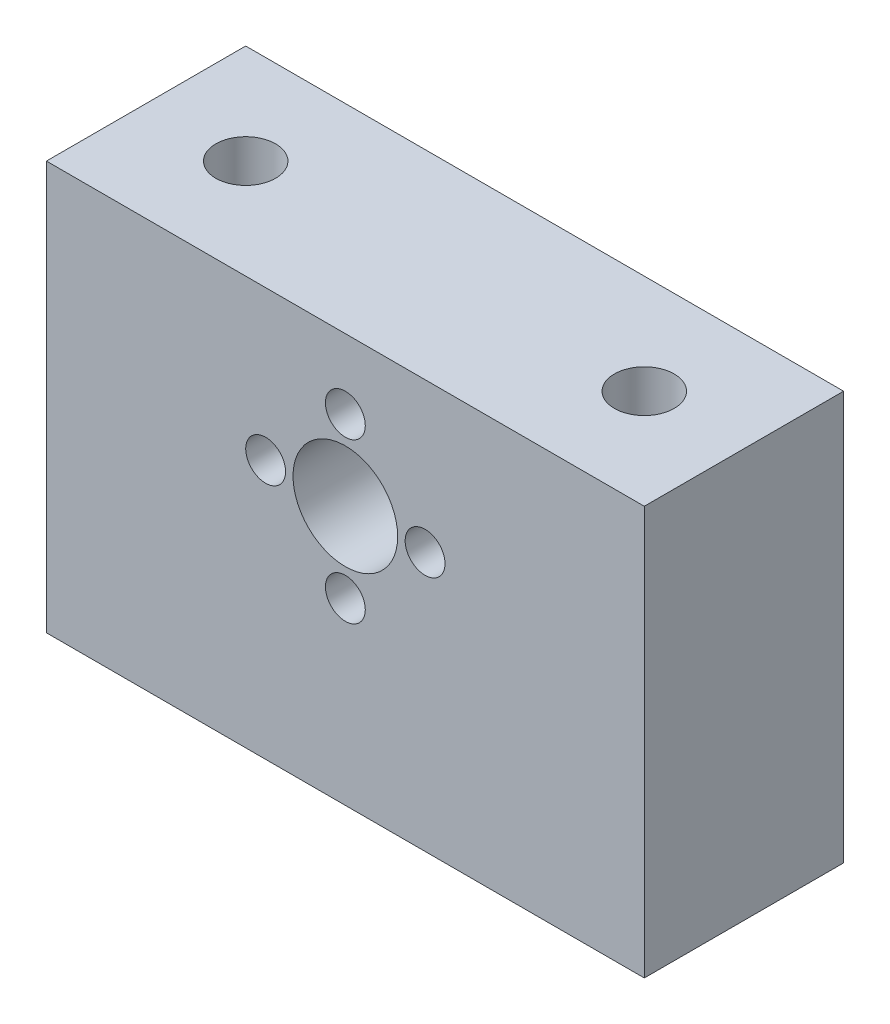
SolidWorks part; units mm, degrees
ref_plane "Front Plane" through (0, 0, 0) normal (0, 0, 1) x (1, 0, 0)
ref_plane "Top Plane" through (0, 0, 0) normal (0, 1, 0) x (1, 0, 0)
ref_plane "Right Plane" through (0, 0, 0) normal (1, 0, 0) x (0, 0, -1)
sketch "Sketch1" plane through (0, 0, 0) normal (0, 0, 1) x (1, 0, 0)
  line L0 (0, -438.3722) -> (0, 21480.2356) construction
  line L1 (-438.3722, 0) -> (21480.2356, 0) construction
  line L3 (-30, -26) -> (30, -26)
  line L4 (-30, -26) -> (-30, 15)
  line L5 (-30, 15) -> (30, 15)
  line L6 (30, -26) -> (30, 15)
  circle A0 centre (0, 0) radius 5.25
  circle A1 centre (0, 0) radius 8 construction
  circle A2 centre (0, 8) radius 2
  circle A3 centre (8, 0) radius 2
  circle A4 centre (0, -8) radius 2
  circle A5 centre (-8, 0) radius 2
  point P4 (0, 0)
  point P24 (0, 0)
  dimension "D2" = 10.5
  dimension "D4" = 16
  dimension "D5" = 4
  dimension "D7" = 8
  dimension "D8" = 8
  dimension "D1" = 15
  dimension "D3" = 60
  dimension "D9" = 26
  dimension "D10" = 30
  dimension "D6" = 4
extrude "Boss-Extrude1" add sketch "Sketch1" along normal blind 20
sketch "Sketch2" plane through (0, 15, 0) normal (0, 1, 0) x (1, 0, 0)
  line L0 (0, -1000) -> (0, 49000) construction
  line L1 (-1030, -10) -> (48970, -10) construction
  line L2 (-30, -20) -> (-30, 0) construction
  circle A0 centre (-20, -10) radius 3
  circle A1 centre (20, -10) radius 3
  point P8 (-30, -10)
  dimension "D2" = 6
  dimension "D1" = 10
extrude "Cut-Extrude1" cut sketch "Sketch2" against normal through all
